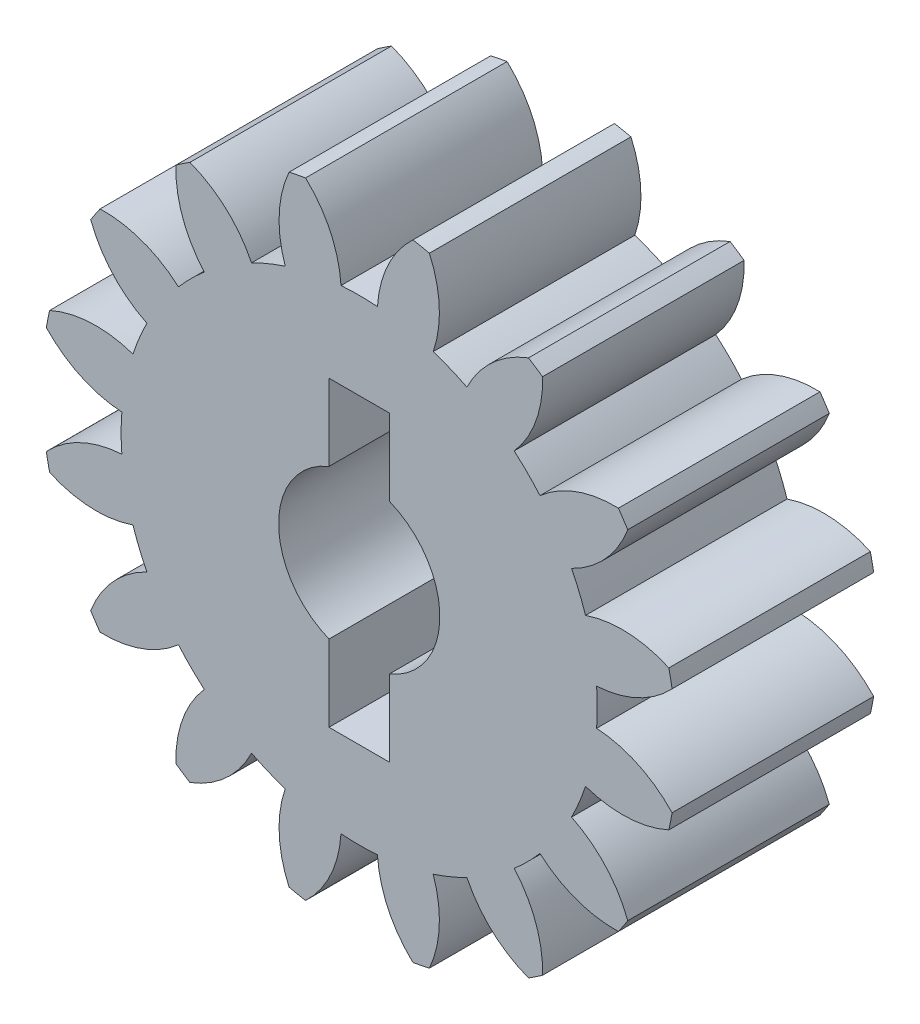
SolidWorks part; units mm, degrees
ref_plane "Front Plane" through (0, 0, 0) normal (0, 0, 1) x (1, 0, 0)
ref_plane "Top Plane" through (0, 0, 0) normal (0, 1, 0) x (1, 0, 0)
ref_plane "Right Plane" through (0, 0, 0) normal (1, 0, 0) x (0, 0, -1)
sketch "Sketch1" plane through (0, 0, 0) normal (0, 0, 1) x (1, 0, 0)
  line L0 (-3, 15) -> (3, 15)
  line L1 (-3, 15) -> (-3, 7.4162)
  line L2 (-3, -15) -> (3, -15)
  line L3 (3, 15) -> (3, 7.4162)
  line L6 (3, -7.4162) -> (3, -15)
  line L9 (-3, -7.4162) -> (-3, -15)
  arc A0 (-31.0469, 5.3236) -> (-23.5546, 1.8098) centre (-22.8815, 12.9895) ccw
  arc A1 (-23.5546, 1.8098) -> (-23.5546, -1.8098) centre (0, 0) ccw
  arc A2 (-23.5546, -1.8098) -> (-31.0469, -5.3236) centre (-22.8815, -12.9895) ccw
  arc A3 (-31.0469, -5.3236) -> (-30.7208, -6.9627) centre (0, 0) ccw
  arc A4 (-30.7208, -6.9627) -> (-22.4542, -7.3419) centre (-26.1106, 3.2444) ccw
  arc A5 (-22.4542, -7.3419) -> (-21.069, -10.686) centre (0, 0) ccw
  arc A6 (-21.069, -10.686) -> (-26.6463, -16.7995) centre (-16.1688, -20.7571) ccw
  arc A7 (-26.6463, -16.7995) -> (-25.7178, -18.1891) centre (0, 0) ccw
  arc A8 (-25.7178, -18.1891) -> (-17.9353, -15.3759) centre (-25.3646, -6.9947) ccw
  arc A9 (-17.9353, -15.3759) -> (-15.3759, -17.9353) centre (0, 0) ccw
  arc A10 (-15.3759, -17.9353) -> (-18.1891, -25.7178) centre (-6.9947, -25.3646) ccw
  arc A11 (-18.1891, -25.7178) -> (-16.7995, -26.6463) centre (0, 0) ccw
  arc A12 (-16.7995, -26.6463) -> (-10.686, -21.069) centre (-20.7571, -16.1688) ccw
  arc A13 (-10.686, -21.069) -> (-7.3419, -22.4542) centre (0, 0) ccw
  arc A14 (-7.3419, -22.4542) -> (-6.9627, -30.7208) centre (3.2444, -26.1106) ccw
  arc A15 (-6.9627, -30.7208) -> (-5.3236, -31.0469) centre (0, 0) ccw
  arc A16 (-5.3236, -31.0469) -> (-1.8098, -23.5546) centre (-12.9895, -22.8815) ccw
  arc A17 (-1.8098, -23.5546) -> (1.8098, -23.5546) centre (0, 0) ccw
  arc A18 (1.8098, -23.5546) -> (5.3236, -31.0469) centre (12.9895, -22.8815) ccw
  arc A19 (5.3236, -31.0469) -> (6.9627, -30.7208) centre (0, 0) ccw
  arc A20 (6.9627, -30.7208) -> (7.3419, -22.4542) centre (-3.2444, -26.1106) ccw
  arc A21 (7.3419, -22.4542) -> (10.686, -21.069) centre (0, 0) ccw
  arc A22 (10.686, -21.069) -> (16.7995, -26.6463) centre (20.7571, -16.1688) ccw
  arc A23 (16.7995, -26.6463) -> (18.1891, -25.7178) centre (0, 0) ccw
  arc A24 (18.1891, -25.7178) -> (15.3759, -17.9353) centre (6.9947, -25.3646) ccw
  arc A25 (15.3759, -17.9353) -> (17.9353, -15.3759) centre (0, 0) ccw
  arc A26 (17.9353, -15.3759) -> (25.7178, -18.1891) centre (25.3646, -6.9947) ccw
  arc A27 (25.7178, -18.1891) -> (26.6463, -16.7995) centre (0, 0) ccw
  arc A28 (26.6463, -16.7995) -> (21.069, -10.686) centre (16.1688, -20.7571) ccw
  arc A29 (21.069, -10.686) -> (22.4542, -7.3419) centre (0, 0) ccw
  arc A30 (22.4542, -7.3419) -> (30.7208, -6.9627) centre (26.1106, 3.2444) ccw
  arc A31 (30.7208, -6.9627) -> (31.0469, -5.3236) centre (0, 0) ccw
  arc A32 (31.0469, -5.3236) -> (23.5546, -1.8098) centre (22.8815, -12.9895) ccw
  arc A33 (23.5546, -1.8098) -> (23.5546, 1.8098) centre (0, 0) ccw
  arc A34 (23.5546, 1.8098) -> (31.0469, 5.3236) centre (22.8815, 12.9895) ccw
  arc A35 (31.0469, 5.3236) -> (30.7208, 6.9627) centre (0, 0) ccw
  arc A36 (30.7208, 6.9627) -> (22.4542, 7.3419) centre (26.1106, -3.2444) ccw
  arc A37 (22.4542, 7.3419) -> (21.069, 10.686) centre (0, 0) ccw
  arc A38 (21.069, 10.686) -> (26.6463, 16.7995) centre (16.1688, 20.7571) ccw
  arc A39 (26.6463, 16.7995) -> (25.7178, 18.1891) centre (0, 0) ccw
  arc A40 (25.7178, 18.1891) -> (17.9353, 15.3759) centre (25.3646, 6.9947) ccw
  arc A41 (17.9353, 15.3759) -> (15.3759, 17.9353) centre (0, 0) ccw
  arc A42 (15.3759, 17.9353) -> (18.1891, 25.7178) centre (6.9947, 25.3646) ccw
  arc A43 (18.1891, 25.7178) -> (16.7995, 26.6463) centre (0, 0) ccw
  arc A44 (16.7995, 26.6463) -> (10.686, 21.069) centre (20.7571, 16.1688) ccw
  arc A45 (10.686, 21.069) -> (7.3419, 22.4542) centre (0, 0) ccw
  arc A46 (7.3419, 22.4542) -> (6.9627, 30.7208) centre (-3.2444, 26.1106) ccw
  arc A47 (6.9627, 30.7208) -> (5.3236, 31.0469) centre (0, 0) ccw
  arc A48 (5.3236, 31.0469) -> (1.8098, 23.5546) centre (12.9895, 22.8815) ccw
  arc A49 (1.8098, 23.5546) -> (-1.8098, 23.5546) centre (0, 0) ccw
  arc A50 (-1.8098, 23.5546) -> (-5.3236, 31.0469) centre (-12.9895, 22.8815) ccw
  arc A51 (-5.3236, 31.0469) -> (-6.9627, 30.7208) centre (0, 0) ccw
  arc A52 (-6.9627, 30.7208) -> (-7.3419, 22.4542) centre (3.2444, 26.1106) ccw
  arc A53 (-7.3419, 22.4542) -> (-10.686, 21.069) centre (0, 0) ccw
  arc A54 (-10.686, 21.069) -> (-16.7995, 26.6463) centre (-20.7571, 16.1688) ccw
  arc A55 (-16.7995, 26.6463) -> (-18.1891, 25.7178) centre (0, 0) ccw
  arc A56 (-18.1891, 25.7178) -> (-15.3759, 17.9353) centre (-6.9947, 25.3646) ccw
  arc A57 (-15.3759, 17.9353) -> (-17.9353, 15.3759) centre (0, 0) ccw
  arc A58 (-17.9353, 15.3759) -> (-25.7178, 18.1891) centre (-25.3646, 6.9947) ccw
  arc A59 (-25.7178, 18.1891) -> (-26.6463, 16.7995) centre (0, 0) ccw
  arc A60 (-26.6463, 16.7995) -> (-21.069, 10.686) centre (-16.1688, 20.7571) ccw
  arc A61 (-21.069, 10.686) -> (-22.4542, 7.3419) centre (0, 0) ccw
  arc A62 (-22.4542, 7.3419) -> (-30.7208, 6.9627) centre (-26.1106, -3.2444) ccw
  arc A63 (-30.7208, 6.9627) -> (-31.0469, 5.3236) centre (0, 0) ccw
  arc A64 (-3, 7.4162) -> (-3, -7.4162) centre (0, 0) ccw
  arc A65 (3, -7.4162) -> (3, 7.4162) centre (0, 0) ccw
  point P129 (0, 0)
  dimension "D3" = 16
  dimension "D4" = 3.6196
  dimension "D5" = 1.8098
  dimension "D6" = 1.6391
  dimension "D7" = 11.2
  dimension "D8" = 23.5546
  dimension "D9" = 1.6712
  dimension "D1" = 30
  dimension "D2" = 6
  dimension "D10" = 8.2667
  dimension "D13" = 7.4923
extrude "Boss-Extrude1" add sketch "Sketch1" along normal blind 20
